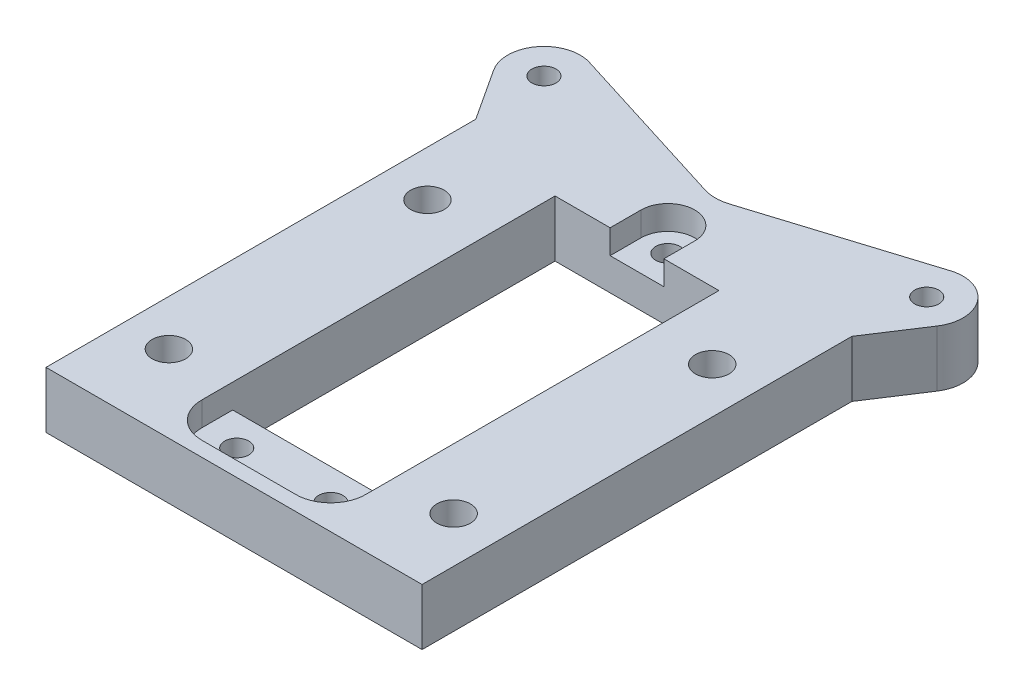
SolidWorks part; units mm, degrees
ref_plane "Front Plane" through (0, 0, 0) normal (0, 0, 1) x (1, 0, 0)
ref_plane "Top Plane" through (0, 0, 0) normal (0, 1, 0) x (1, 0, 0)
ref_plane "Right Plane" through (0, 0, 0) normal (1, 0, 0) x (0, 0, -1)
sketch "Sketch1" plane through (0, 0, 0) normal (0, 1, 0) x (1, 0, 0)
  line L4 (6.1, -12) -> (6.1, 12)
  line L5 (-6.1, -12) -> (6.1, -12)
  line L6 (-6.1, 12) -> (-6.1, -12)
  line L14 (14, -18) -> (14, 14)
  line L15 (14, 14) -> (16.5106, 17.8441)
  line L16 (13.3797, 21.8764) -> (0, 17.6909)
  line L17 (0, 17.6909) -> (-13.3797, 21.8764)
  line L18 (-16.5106, 17.8441) -> (-14, 14)
  line L19 (-14, 14) -> (-14, -18)
  line L20 (-14, -18) -> (14, -18)
  line L21 (6.1, 12) -> (-6.1, 12)
  arc A4 (16.5106, 17.8441) -> (13.3797, 21.8764) centre (14.25, 19.3205) ccw
  arc A5 (-13.3797, 21.8764) -> (-16.5106, 17.8441) centre (-14.25, 19.3205) ccw
  circle A14 centre (-10.6, 7) radius 1.25
  circle A15 centre (-10.6, -12.25) radius 1.25
  circle A16 centre (-3.5, -14.3) radius 0.9
  circle A18 centre (3.5, -14.3) radius 0.9
  circle A19 centre (10.6, -12.25) radius 1.25
  circle A20 centre (10.6, 7) radius 1.25
  circle A22 centre (0, 14.3) radius 0.9
  circle A25 centre (-14.25, 19.3205) radius 0.9
  circle A27 centre (14.25, 19.3205) radius 0.9
  point P22 (0, -12)
  dimension "D3" = 2.5
  dimension "D4" = 1.8
  dimension "D5" = 1.8
  dimension "D6" = 2.7
  dimension "D22" = 5.75
  dimension "D15" = 3.4
  dimension "D9" = 3.4
  dimension "D1" = 24
  dimension "D2" = 12.2
  dimension "D7" = 3.5
  dimension "D8" = 14.3
  dimension "D10" = 14
  dimension "D11" = 13.3797
  dimension "D12" = 14.25
  dimension "D13" = 16.5106
  dimension "D14" = 3.5
  dimension "D16" = 7
  dimension "D17" = 12
  dimension "D18" = 14
  dimension "D20" = 17.6909
  dimension "D21" = 18
  dimension "D25" = 14.3
extrude "Boss-Extrude2" add sketch "Sketch1" along normal blind 4.2 contours L18 L19 L20 L14 L15 A4 L16 L17 A5
fillet "Fillet1" radius 3 1 edges at (0, 2.1, -17.6909)
sketch "Sketch2" plane through (0, 4.2, 0) normal (0, 1, 0) x (1, 0, 0)
  line L35 (-6.1, -12) -> (-6.1, -14.3)
  line L37 (6.1, -14.3) -> (6.1, -12)
  line L38 (6.1, -12) -> (-6.1, -12)
  line L39 (-3.5, -16.9) -> (3.5, -16.9)
  line L40 (-2, 14.3) -> (-2, 12)
  line L41 (6.1, 12) -> (-6.1, 12) construction
  line L42 (-2, 12) -> (2, 12)
  line L43 (2, 12) -> (2, 14.3)
  arc A11 (6.1, -14.3) -> (3.5, -16.9) centre (3.5, -14.3) cw
  arc A12 (-6.1, -14.3) -> (-3.5, -16.9) centre (-3.5, -14.3) ccw
  arc A13 (-2, 14.3) -> (2, 14.3) centre (0, 14.3) cw
  dimension "D1" = 2
extrude "Cut-Extrude1" cut sketch "Sketch2" against normal blind 1.8
